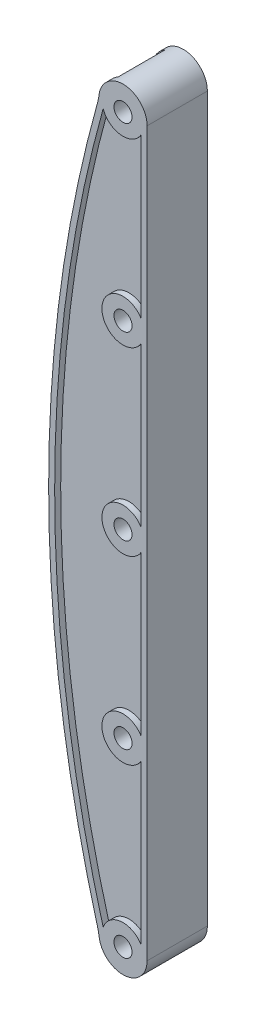
SolidWorks part; units mm, degrees
ref_plane "Front Plane" through (0, 0, 0) normal (0, 0, 1) x (1, 0, 0)
ref_plane "Top Plane" through (0, 0, 0) normal (0, 1, 0) x (1, 0, 0)
ref_plane "Right Plane" through (0, 0, 0) normal (1, 0, 0) x (0, 0, -1)
sketch "Sketch1" plane through (0, 0, 0) normal (0, 0, 1) x (1, 0, 0)
  line L0 (0, 60) -> (0, -60) construction
  line L1 (4, 60) -> (4, -60) construction
  line L2 (-4, 60) -> (-4, -60) construction
  line L3 (4, 60) -> (4, -60)
  circle A0 centre (0, 60) radius 1.5
  circle A1 centre (0, 30) radius 1.5
  circle A2 centre (0, -30) radius 1.5
  circle A3 centre (0, 0) radius 1.5
  circle A4 centre (0, -60) radius 1.5
  arc A5 (-4, 60) -> (4, 60) centre (0, 60) cw
  arc A6 (-4, -60) -> (4, -60) centre (0, -60) ccw
  arc A7 (-4, 60) -> (-4, -60) centre (207.6601, 0) ccw
  dimension "D2" = 3
  dimension "D7" = 220
  dimension "D1" = 120
  dimension "D3" = 30
  dimension "D4" = 30
  dimension "D5" = 4
  dimension "D6" = 4
extrude "Boss-Extrude1" add sketch "Sketch1" along normal mid plane 10
fillet "Fillet1" radius 10 2 edges at (-4, -60, 0) (-4, 60, 0)
sketch "Sketch2" plane through (0, 0, 5) normal (0, 0, 1) x (1, 0, 0)
  line L2 (3, -60) -> (3, 60)
  line L3 (3, -60) -> (3, 60)
  circle A7 centre (0, 60) radius 3.5
  circle A8 centre (0, 60) radius 3.5
  arc A10 (3, 60) -> (-2.9755, 60.3827) centre (0, 60) ccw
  arc A11 (-3.29, 58.8308) -> (-2.9755, 60.3827) centre (-13.8856, 61.7858) ccw
  arc A12 (-3.29, 58.8308) -> (-3.29, -58.8308) centre (207.6601, 0) ccw
  arc A13 (-2.9755, -60.3827) -> (-3.29, -58.8308) centre (-13.8856, -61.7858) ccw
  arc A14 (-2.9755, -60.3827) -> (3, -60) centre (0, -60) ccw
  arc A15 (3, 60) -> (-2.9755, 60.3827) centre (0, 60) ccw
  arc A16 (-3.29, 58.8308) -> (-2.9755, 60.3827) centre (-13.8856, 61.7858) ccw
  arc A17 (-3.29, 58.8308) -> (-3.29, -58.8308) centre (207.6601, 0) ccw
  arc A18 (-2.9755, -60.3827) -> (-3.29, -58.8308) centre (-13.8856, -61.7858) ccw
  arc A19 (-2.9755, -60.3827) -> (3, -60) centre (0, -60) ccw
  circle A20 centre (0, 30) radius 3.5
  circle A21 centre (0, 30) radius 3.5
  circle A23 centre (0, 0) radius 3.5
  circle A24 centre (0, 0) radius 3.5
  circle A26 centre (0, -30) radius 3.5
  circle A27 centre (0, -30) radius 3.5
  circle A29 centre (0, -60) radius 3.5
  circle A30 centre (0, -60) radius 3.5
  dimension "D1" = 1
  dimension "D2" = 2
  dimension "D3" = 2
  dimension "D4" = 2
  dimension "D5" = 2
  dimension "D6" = 2
extrude "Cut-Extrude1" cut sketch "Sketch2" against normal blind 1 contours A30 L3 A27 A24 A21 A8 A17
sketch "Sketch3" plane through (0, 0, 0) normal (0, 0, 1) x (1, 0, 0)
  line L1 (0.1487, 70) -> (-49.8513, 70)
  line L2 (0.1487, 70) -> (0.1487, -70)
  line L3 (0.1487, -70) -> (-49.8513, -70)
  line L4 (-49.8513, 70) -> (-49.8513, -70)
  arc A0 (-3.2939, 58.8167) -> (-3.2939, -58.8167) centre (207.6601, 0) ccw construction
  arc A1 (-3.2939, 58.8167) -> (-3.2939, -58.8167) centre (207.6601, 0) ccw
  circle A2 centre (207.6601, 0) radius 219
  dimension "D1" = 50
  dimension "D2" = 140
extrude "Cut-Extrude2" cut sketch "Sketch3" against normal mid plane 7.8 contours A2 L1 L4 L3 A1
